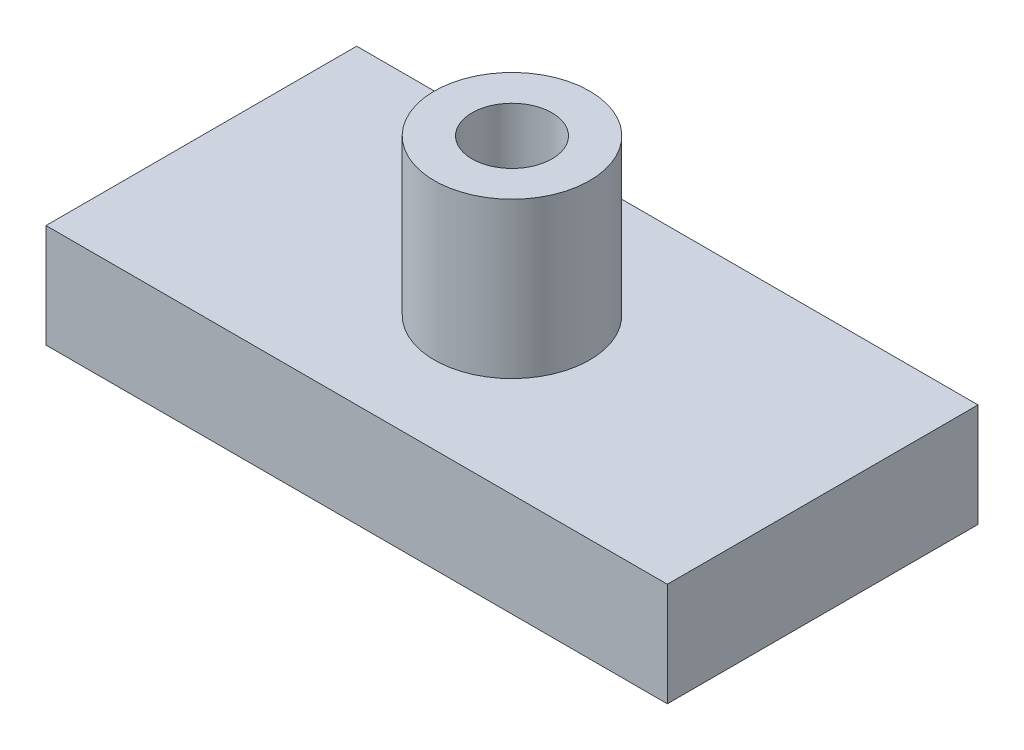
SolidWorks part; units mm, degrees
ref_plane "Front Plane" through (0, 0, 0) normal (0, 0, 1) x (1, 0, 0)
ref_plane "Top Plane" through (0, 0, 0) normal (0, 1, 0) x (1, 0, 0)
ref_plane "Right Plane" through (0, 0, 0) normal (1, 0, 0) x (0, 0, -1)
sketch "Sketch1" plane through (0, 0, 0) normal (0, 1, 0) x (1, 0, 0)
  line L1 (0, 0) -> (38.1, 0)
  line L2 (0, 0) -> (0, 19.05)
  line L3 (0, 19.05) -> (38.1, 19.05)
  line L4 (38.1, 0) -> (38.1, 19.05)
  dimension "D1" = 38.1
  dimension "D2" = 19.05
extrude "Boss-Extrude1" add sketch "Sketch1" along normal blind 6.35
sketch "Sketch2" plane through (0, 6.35, 0) normal (0, 1, 0) x (1, 0, 0)
  line L0 (0, 0) -> (38.1, 19.05) construction
  circle A0 centre (19.05, 9.525) radius 4.7625
  dimension "D1" = 9.525
extrude "Boss-Extrude2" add sketch "Sketch2" along normal blind 9.525
sketch "Sketch3" plane through (0, 15.875, 0) normal (0, 1, 0) x (1, 0, 0)
  circle A0 centre (19.05, 9.525) radius 2.4511
  dimension "D1" = 4.9022
extrude "Cut-Extrude1" cut sketch "Sketch3" against normal through all contours A0
